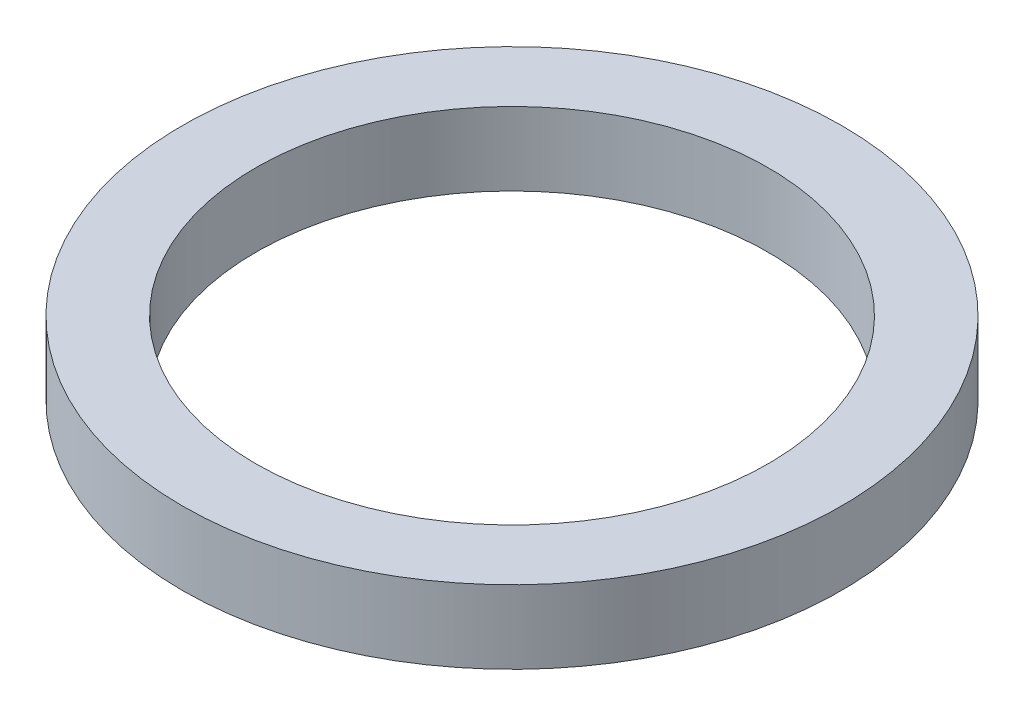
SolidWorks part; units mm, degrees
ref_plane "前视基准面" through (0, 0, 0) normal (0, 0, 1) x (1, 0, 0)
ref_plane "上视基准面" through (0, 0, 0) normal (0, 1, 0) x (1, 0, 0)
ref_plane "右视基准面" through (0, 0, 0) normal (1, 0, 0) x (0, 0, -1)
other "Configuration Table"
sketch "草图1" plane through (0, 0, 0) normal (0, 1, 0) x (1, 0, 0)
  circle A0 centre (0, 0) radius 17.5
  circle A1 centre (0, 0) radius 22.5
  dimension "D1" = 35
  dimension "D2" = 45
extrude "凸台-拉伸1" add sketch "草图1" along normal blind 5
